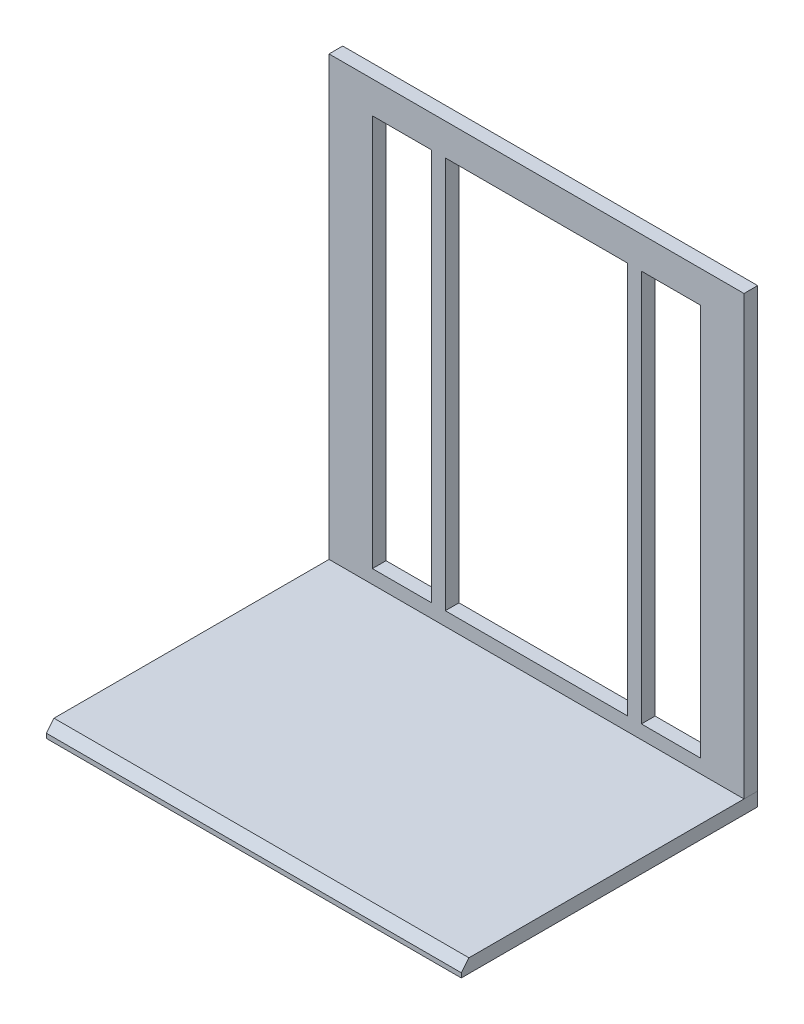
SolidWorks part; units mm, degrees
ref_plane "Front" through (0, 0, 0) normal (0, 0, 1) x (1, 0, 0)
ref_plane "Top" through (0, 0, 0) normal (0, 1, 0) x (1, 0, 0)
ref_plane "Right" through (0, 0, 0) normal (1, 0, 0) x (0, 0, -1)
sketch "Sketch1" plane through (0, 0, 0) normal (0, 0, 1) x (1, 0, 0)
  line L0 (0, 50.8) -> (0, 0) construction
  line L1 (-508, 1092.2) -> (508, 1092.2)
  line L2 (-508, 1092.2) -> (-508, -1092.2)
  line L3 (-508, -1092.2) -> (508, -1092.2)
  line L4 (508, 1092.2) -> (508, -1092.2)
  line L5 (-508, 1092.2) -> (508, -1092.2) construction
  line L6 (-508, -1092.2) -> (508, 1092.2) construction
  line L7 (-1155.7, 1270) -> (1155.7, 1270)
  line L8 (-1155.7, 1270) -> (-1155.7, -1168.4)
  line L9 (-1155.7, -1168.4) -> (1155.7, -1168.4)
  line L10 (1155.7, 1270) -> (1155.7, -1168.4)
  line L11 (-1155.7, 1270) -> (1155.7, -1168.4) construction
  line L12 (-1155.7, -1168.4) -> (1155.7, 1270) construction
  line L13 (0, 0) -> (0, -1092.2) construction
  line L14 (-914.4, 1092.2) -> (-584.2, 1092.2)
  line L15 (-914.4, 1092.2) -> (-914.4, -1092.2)
  line L16 (-914.4, -1092.2) -> (-584.2, -1092.2)
  line L17 (-584.2, 1092.2) -> (-584.2, -1092.2)
  line L18 (914.4, -1092.2) -> (584.2, -1092.2)
  line L19 (584.2, 1092.2) -> (584.2, -1092.2)
  line L20 (914.4, 1092.2) -> (584.2, 1092.2)
  line L21 (914.4, 1092.2) -> (914.4, -1092.2)
  point P0 (0, 0)
  point P6 (0, 50.8)
  dimension "D1" = 1016
  dimension "D2" = 2311.4
  dimension "D3" = 2438.4
  dimension "D4" = 76.2
  dimension "D5" = 2184.4
  dimension "D6" = 330.2
  dimension "D7" = 76.2
extrude "Boss-Extrude1" add sketch "Sketch1" along normal blind 76.2
sketch "Sketch2" plane through (0, 0, 0) normal (0, 0, -1) x (-1, 0, 0)
  line L0 (-1155.7, -1168.4) -> (-1155.7, 1270) construction
  line L1 (1155.7, -1168.4) -> (-1155.7, -1168.4)
  line L2 (1155.7, -1168.4) -> (1155.7, -1244.6)
  line L3 (1155.7, -1244.6) -> (-1155.7, -1244.6)
  line L4 (-1155.7, -1168.4) -> (-1155.7, -1244.6)
  dimension "D1" = 76.2
extrude "Boss-Extrude2" add sketch "Sketch2" against normal blind 1651 separate body
chamfer "Chamfer1" distance 50.8 angle 40 1 edges at (0, -1168.4, 1651)
